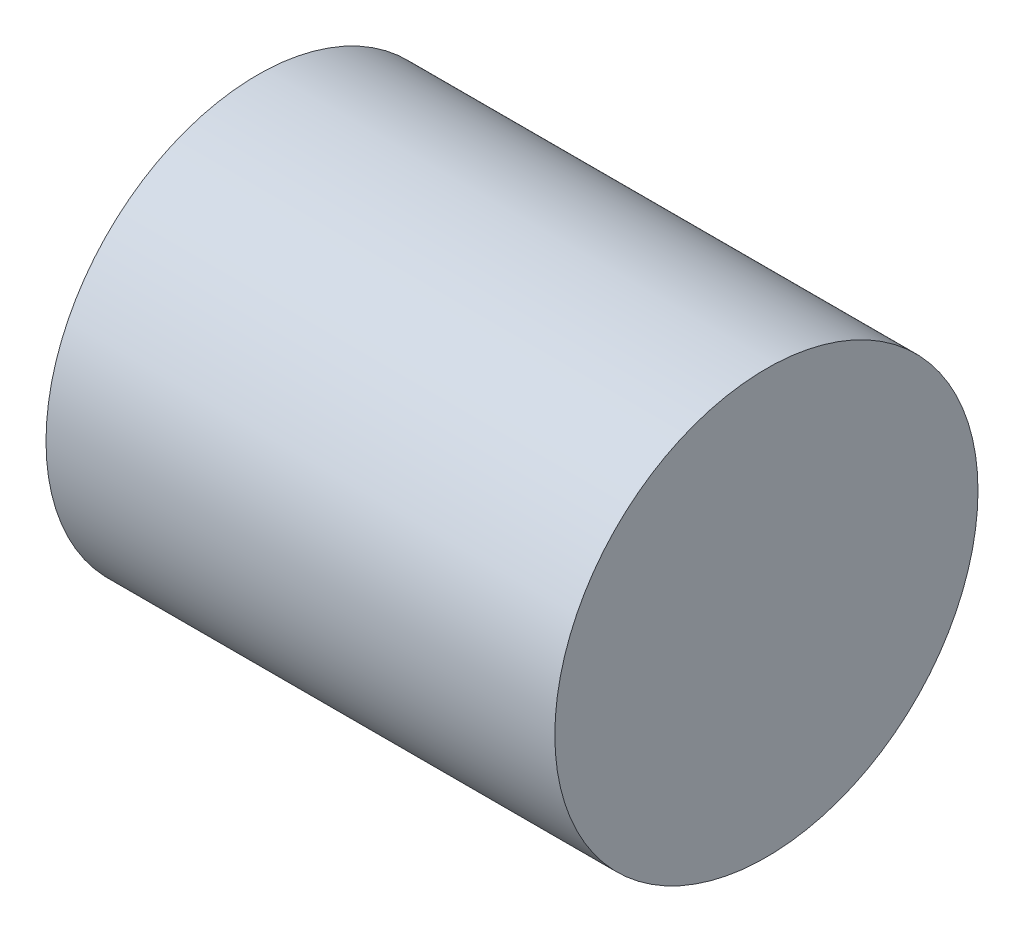
SolidWorks part; units mm, degrees
ref_plane "Front Plane" through (0, 0, 0) normal (0, 0, 1) x (1, 0, 0)
ref_plane "Top Plane" through (0, 0, 0) normal (0, 1, 0) x (1, 0, 0)
ref_plane "Right Plane" through (0, 0, 0) normal (1, 0, 0) x (0, 0, -1)
sketch "Sketch1" plane through (0, 0, 0) normal (1, 0, 0) x (0, 0, -1)
  circle A0 centre (0, 0) radius 4.99
  dimension "D1" = 9.98
extrude "Boss-Extrude1" add sketch "Sketch1" along normal blind 12
